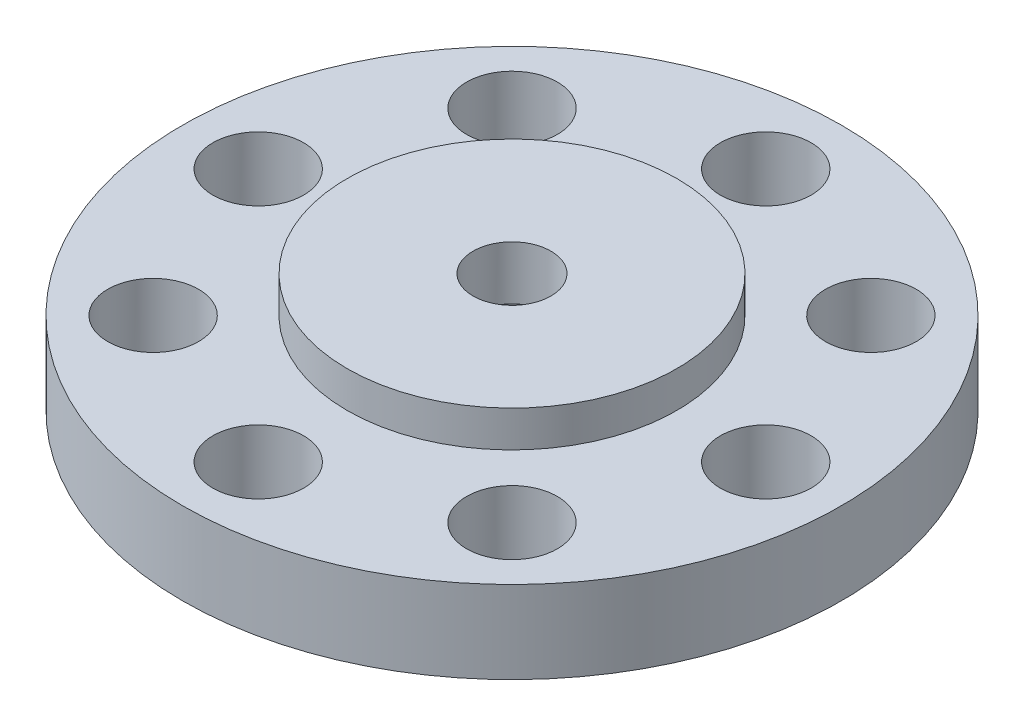
SolidWorks part; units mm, degrees
ref_plane "Front Plane" through (0, 0, 0) normal (0, 0, 1) x (1, 0, 0)
ref_plane "Top Plane" through (0, 0, 0) normal (0, 1, 0) x (1, 0, 0)
ref_plane "Right Plane" through (0, 0, 0) normal (1, 0, 0) x (0, 0, -1)
sketch "Sketch1" plane through (0, 0, 0) normal (0, 1, 0) x (1, 0, 0)
  circle A0 centre (0, 0) radius 12.7
  dimension "D1" = 25.4
extrude "Boss-Extrude1" add sketch "Sketch1" against normal blind 3.175
sketch "Sketch2" plane through (0, 0, 0) normal (0, 1, 0) x (1, 0, 0)
  circle A0 centre (0, 0) radius 6.35
  dimension "D1" = 12.7
extrude "Boss-Extrude2" add sketch "Sketch2" along normal blind 1.397
sketch "Sketch3" plane through (0, 1.397, 0) normal (0, 1, 0) x (1, 0, 0)
  circle A0 centre (0, 0) radius 1.5
  dimension "D1" = 3
extrude "Cut-Extrude1" cut sketch "Sketch3" against normal through all both and the other way through all
sketch "Sketch4" plane through (0, 0, 0) normal (0, 1, 0) x (1, 0, 0)
  circle A0 centre (0, -9.779) radius 1.75
  dimension "D1" = 3.5
  dimension "D2" = 9.779
  dimension "D3" = 0
extrude "Cut-Extrude2" cut sketch "Sketch4" against normal through all both and the other way through all
pattern_circular "CirPattern1" count 8 over 360 about axis through (0, 0, 0) along (0, 1, 0) of "Cut-Extrude2"
sketch "Sketch5" plane through (0, -3.175, 0) normal (0, -1, 0) x (1, 0, 0)
  circle A0 centre (0, 0) radius 2.5
  dimension "D1" = 5
extrude "Cut-Extrude3" cut sketch "Sketch5" against normal blind 2.5
